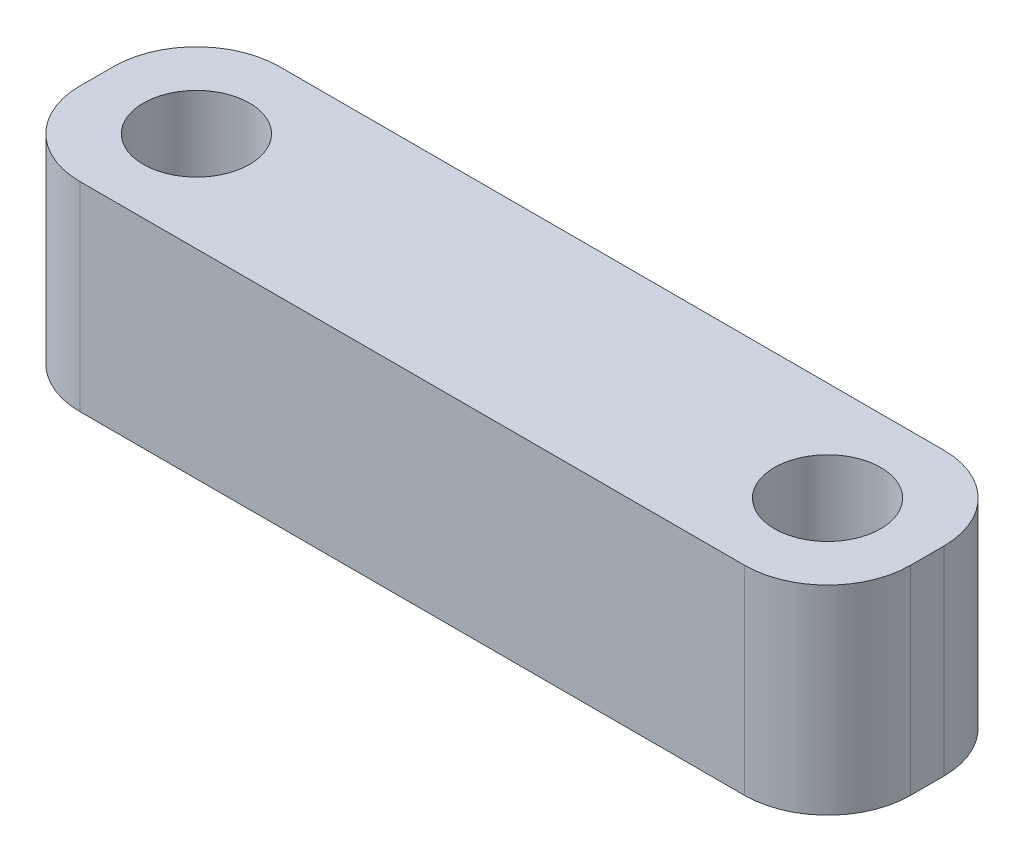
SolidWorks part; units mm, degrees
ref_plane "Front Plane" through (0, 0, 0) normal (0, 0, 1) x (1, 0, 0)
ref_plane "Top Plane" through (0, 0, 0) normal (0, 1, 0) x (1, 0, 0)
ref_plane "Right Plane" through (0, 0, 0) normal (1, 0, 0) x (0, 0, -1)
sketch "Sketch1" plane through (0, 0, 0) normal (0, 1, 0) x (1, 0, 0)
  line L1 (-12.5, -3) -> (12.5, -3)
  line L2 (-12.5, -3) -> (-12.5, 3)
  line L3 (-12.5, 3) -> (12.5, 3)
  line L4 (12.5, -3) -> (12.5, 3)
  line L5 (-12.5, -3) -> (12.5, 3) construction
  line L6 (-12.5, 3) -> (12.5, -3) construction
  point P0 (0, 0)
  dimension "D1" = 6
  dimension "D2" = 25
extrude "Boss-Extrude1" add sketch "Sketch1" along normal mid plane 6
sketch "Sketch2" plane through (0, 3, 0) normal (0, 1, 0) x (1, 0, 0)
  line L1 (12.5, -3) -> (12.5, 3) construction
  line L2 (-12.5, 3) -> (-12.5, -3) construction
  line L3 (-12.5, 0) -> (-9.5, 0) construction
  line L4 (12.5, 0) -> (9.5, 0) construction
  circle A0 centre (9.5, 0) radius 1.6
  circle A1 centre (-9.5, 0) radius 1.6
  point P7 (12.5, 0)
  point P11 (-12.5, 0)
  dimension "D2" = 3.2
  dimension "D1" = 3
extrude "Cut-Extrude1" cut sketch "Sketch2" against normal through all
fillet "Fillet1" radius 2.5 4 edges at (-12.5, 0, 3) (-12.5, 0, -3) (12.5, 0, -3) (12.5, 0, 3)
